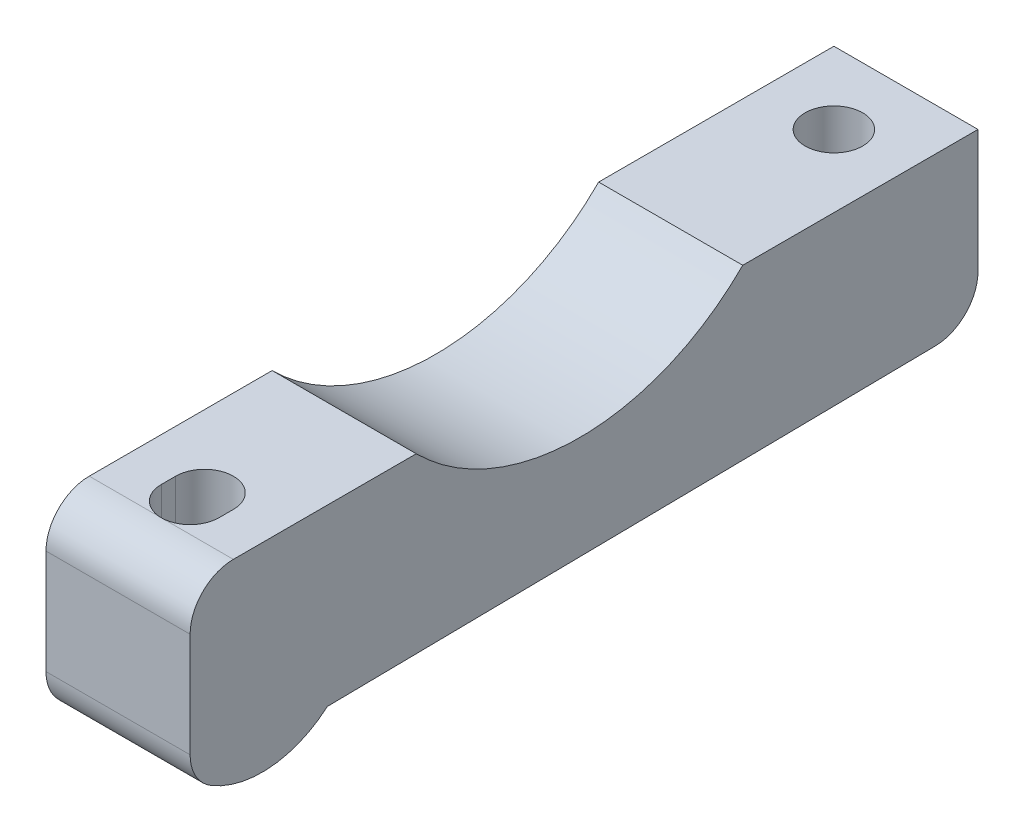
SolidWorks part; units mm, degrees
ref_plane "Plan de face" through (0, 0, 0) normal (0, 0, 1) x (1, 0, 0)
ref_plane "Plan de dessus" through (0, 0, 0) normal (0, 1, 0) x (1, 0, 0)
ref_plane "Plan de droite" through (0, 0, 0) normal (1, 0, 0) x (0, 0, -1)
sketch "Esquisse1" plane through (0, 0, 0) normal (1, 0, 0) x (0, 0, -1)
  line L2 (-87.524, -46.245) -> (-87.524, -38.9998)
  line L3 (-84.524, -35.9998) -> (-70.3692, -35.9998)
  line L4 (-32.8482, -44.5343) -> (-32.8482, -35.9998)
  line L5 (-50.6374, -35.9998) -> (-32.8482, -35.9998)
  line L6 (-78.0003, -48.1039) -> (-35.8077, -47.534)
  line L8 (-82.524, -35.9998) -> (-82.524, -42.9198) construction
  arc A0 (-70.3692, -35.9998) -> (-50.6374, -35.9998) centre (-60.5033, -24.7009) ccw
  arc A2 (-86.0703, -48.8159) -> (-78.0003, -48.1039) centre (-82.524, -42.9198) ccw
  arc A3 (-35.8077, -47.534) -> (-32.8482, -44.5343) centre (-35.8482, -44.5343) ccw
  arc A4 (-86.0703, -48.8159) -> (-87.524, -46.245) centre (-84.524, -46.245) cw
  arc A5 (-87.524, -38.9998) -> (-84.524, -35.9998) centre (-84.524, -38.9998) cw
  point P23 (-87.524, -47.6463)
  point P28 (-87.524, -35.9998)
  dimension "D1" = 5
  dimension "D2" = 6.8803
  dimension "D5" = 3
  dimension "D6" = 3
  dimension "D7" = 3
  dimension "D3" = 11.6465
  dimension "D4" = 12
  dimension "D8" = 17.7892
  dimension "D9" = 42.1926
extrude "Boss.-Extru.1" add sketch "Esquisse1" along normal blind 10
ref_plane "Plan1" through (0, -47.9998, 0) normal (0, 1, 0) x (1, 0, 0)
sketch "Esquisse2" plane through (0, -35.9998, 0) normal (0, 1, 0) x (1, 0, 0)
  line L0 (5, -87.524) -> (5, -82.524) construction
  line L1 (10, -87.524) -> (0, -87.524) construction
  line L2 (5, -82.524) -> (5, -81.524) construction
  line L3 (3, -82.524) -> (3, -81.524)
  line L4 (7, -82.524) -> (7, -81.524)
  line L6 (10, -84.524) -> (0, -84.524) construction
  arc A0 (3, -82.524) -> (7, -82.524) centre (5, -82.524) ccw
  arc A2 (7, -81.524) -> (3, -81.524) centre (5, -81.524) ccw
  dimension "D4" = 2
  dimension "D5" = 1
extrude "Enlèv. mat.-Extru.1" cut sketch "Esquisse2" against normal through all
sketch "Esquisse3" plane through (0, -35.9998, 0) normal (0, 1, 0) x (1, 0, 0)
  line L0 (5, -32.8482) -> (5, -37.8482) construction
  line L1 (10, -32.8482) -> (0, -32.8482) construction
  circle A0 centre (5, -37.8482) radius 2
  dimension "D2" = 4
  dimension "D1" = 5
extrude "Enlèv. mat.-Extru.2" cut sketch "Esquisse3" against normal through all
sketch "Esquisse4" plane through (0, -47.9998, 141.2182) normal (0, 1, 0) x (1, 0, 0)
  line L1 (5, 107.553) -> (1.3775, 105.4615)
  line L2 (1.3775, 105.4615) -> (1.3775, 101.2786)
  line L3 (1.3775, 101.2786) -> (5, 99.1871)
  line L4 (5, 99.1871) -> (8.6225, 101.2786)
  line L5 (8.6225, 101.2786) -> (8.6225, 105.4615)
  line L6 (8.6225, 105.4615) -> (5, 107.553)
  circle A0 centre (5, 103.37) radius 3.6225 construction
  circle A2 centre (5, 103.37) radius 2 construction
  dimension "D1" = 7.245
extrude "Enlèv. mat.-Extru.3" cut sketch "Esquisse4" along normal blind 3.3
sketch "Esquisse5" plane through (10, 0, 0) normal (1, 0, 0) x (0, 0, -1)
  line L0 (-70.3692, -35.9998) -> (-71.8319, -35.9998)
  line L1 (-70.3692, -35.9998) -> (-84.524, -35.9998) construction
  line L2 (-50.6374, -35.9998) -> (-49.1747, -35.9998)
  line L3 (-32.8482, -35.9998) -> (-50.6374, -35.9998) construction
  line L4 (-70.3692, -35.9998) -> (-50.6374, -35.9998)
  line L5 (-60.5033, -24.7009) -> (-60.5033, -35.9998) construction
  arc A0 (-71.8319, -35.9998) -> (-49.1747, -35.9998) centre (-60.5033, -24.7009) ccw
  arc A1 (-70.3692, -35.9998) -> (-50.6374, -35.9998) centre (-60.5033, -24.7009) ccw construction
  dimension "D1" = 1
  dimension "D2" = 11.2988
extrude "Enlèv. mat.-Extru.4" cut sketch "Esquisse5" against normal through all
